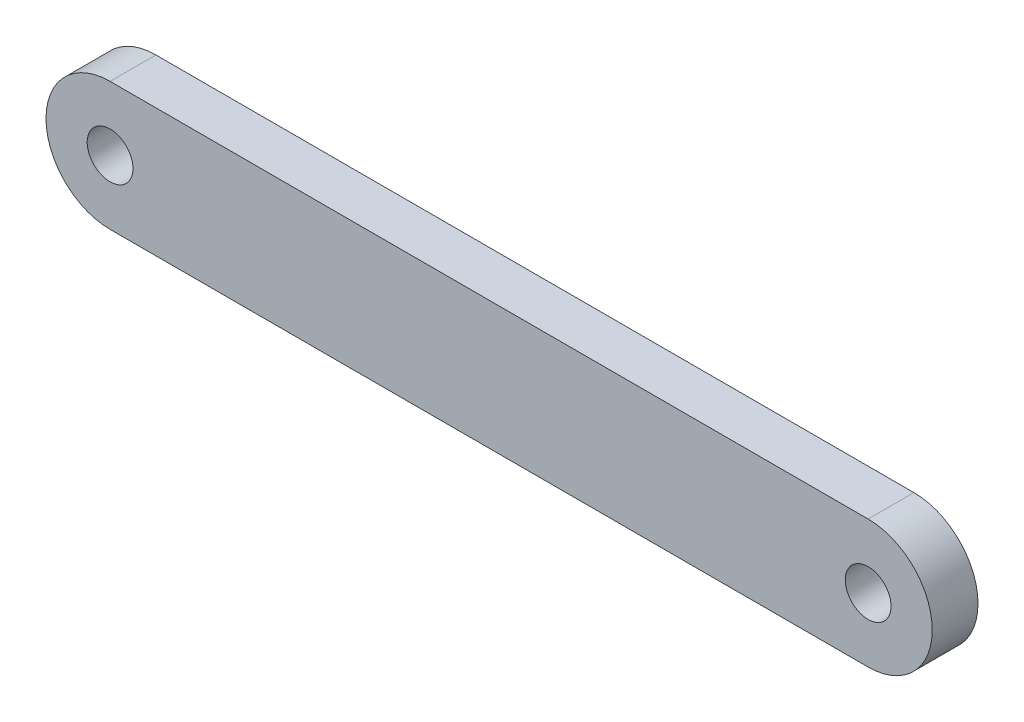
SolidWorks part; units mm, degrees
ref_plane "Front Plane" through (0, 0, 0) normal (0, 0, 1) x (1, 0, 0)
ref_plane "Top Plane" through (0, 0, 0) normal (0, 1, 0) x (1, 0, 0)
ref_plane "Right Plane" through (0, 0, 0) normal (1, 0, 0) x (0, 0, -1)
sketch "Sketch1" plane through (0, 0, 0) normal (0, 0, 1) x (1, 0, 0)
  line L0 (-49.911, -8.7733) -> (55.232, -8.7733)
  line L1 (-49.911, 9.0067) -> (55.232, 9.0067)
  line L2 (-49.911, -8.7733) -> (55.232, 9.0067) construction
  line L3 (-49.911, 9.0067) -> (55.232, -8.7733) construction
  arc A0 (-49.911, 9.0067) -> (-49.911, -8.7733) centre (-49.911, 0.1167) ccw
  arc A1 (55.232, 9.0067) -> (55.232, -8.7733) centre (55.232, 0.1167) cw
  circle A2 centre (-49.911, 0.1167) radius 3.175
  circle A3 centre (55.232, 0.1167) radius 3.175
  point P0 (2.6605, 0.1167)
  dimension "D3" = 6.35
  dimension "D1" = 105.143
  dimension "D2" = 17.78
extrude "Boss-Extrude1" add sketch "Sketch1" along normal blind 6.35
